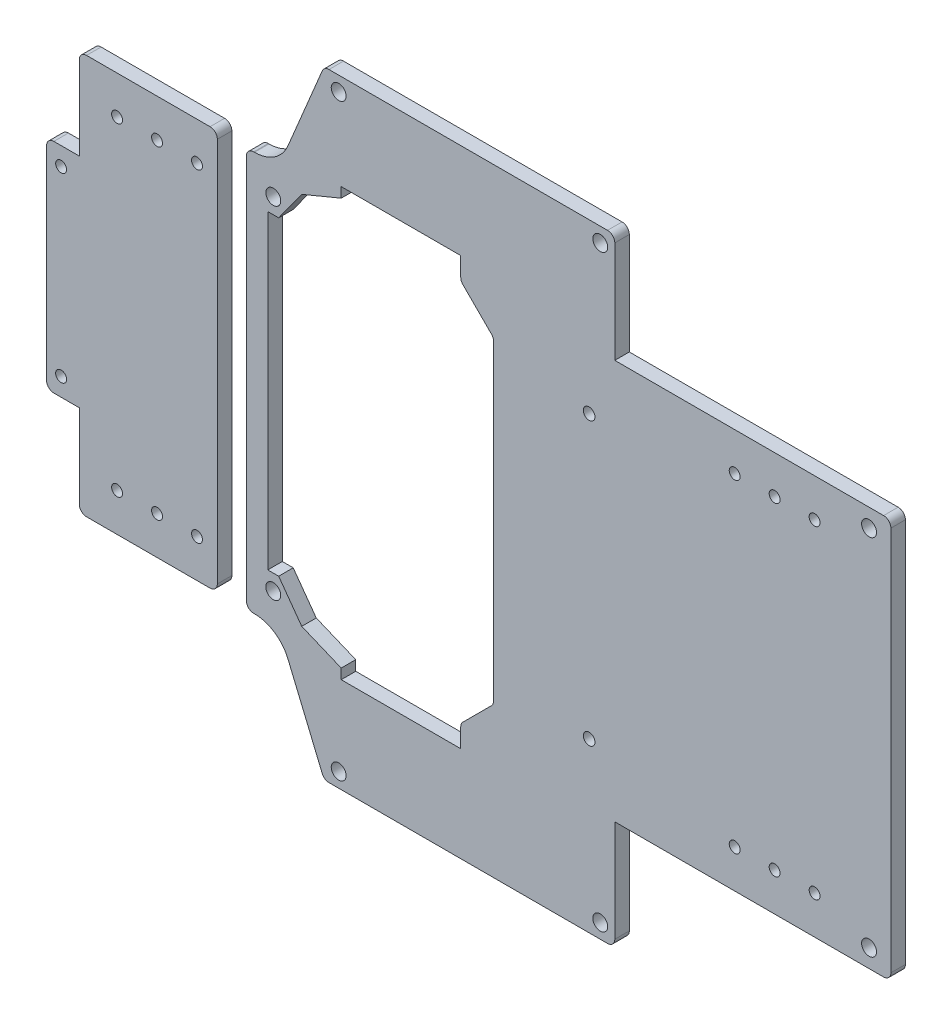
SolidWorks part; units mm, degrees
ref_plane "前视基准面" through (0, 0, 0) normal (0, 0, 1) x (1, 0, 0)
ref_plane "上视基准面" through (0, 0, 0) normal (0, 1, 0) x (1, 0, 0)
ref_plane "右视基准面" through (0, 0, 0) normal (1, 0, 0) x (0, 0, -1)
other "Configuration Table"
sketch "草图1" plane through (0, 0, 0) normal (0, 0, 1) x (1, 0, 0)
  line L16 (-45.366, -102.5649) -> (-42.366, -102.5649)
  line L17 (-45.366, -61.4682) -> (-45.366, -102.5649)
  line L18 (7.7514, -61.4682) -> (-45.366, -61.4682)
  line L19 (7.7514, -111.3467) -> (7.7514, -61.4682)
  line L20 (2.1538, -115.8547) -> (7.7514, -111.3467)
  line L21 (-25.1515, -115.8547) -> (2.1538, -115.8547)
  line L22 (-36.0216, -111.3467) -> (-25.1515, -115.8547)
  line L23 (-42.366, -102.5649) -> (-36.0216, -111.3467)
  line L32 (2.1538, -3.8547) -> (-25.1515, -3.8547)
  line L33 (7.7514, -8.3627) -> (2.1538, -3.8547)
  line L34 (7.7514, -58.2412) -> (7.7514, -8.3627)
  line L35 (-45.366, -58.2412) -> (7.7514, -58.2412)
  line L36 (-45.366, -17.1445) -> (-45.366, -58.2412)
  line L37 (-42.366, -17.1445) -> (-45.366, -17.1445)
  line L38 (-36.0216, -8.3627) -> (-42.366, -17.1445)
  line L39 (-25.1515, -3.8547) -> (-36.0216, -8.3627)
  line L48 (-97.2501, -29.8547) -> (-104.2501, -29.8547)
  line L49 (-106.2501, -31.8547) -> (-106.2501, -87.8547)
  line L50 (-104.2501, -89.8547) -> (-97.2501, -89.8547)
  line L51 (-97.2501, -89.8547) -> (-97.2501, -112.8547)
  line L52 (-95.2501, -114.8547) -> (-61.2501, -114.8547)
  line L53 (-59.2501, -112.8547) -> (-59.2501, -6.8547)
  line L54 (-61.2501, -4.8547) -> (-95.2501, -4.8547)
  line L55 (-97.2501, -6.8547) -> (-97.2501, -29.8547)
  line L72 (-51.2501, -6.8547) -> (-51.2501, -112.8547)
  line L73 (-49.2501, -114.8547) -> (-49.0398, -114.8547)
  line L74 (-39.8127, -120.9997) -> (-30.3597, -143.6257)
  line L75 (-28.5143, -144.8547) -> (48.1538, -144.8547)
  line L76 (50.1538, -142.8547) -> (50.1538, -114.8547)
  line L77 (50.1538, -114.8547) -> (124.1538, -114.8547)
  line L78 (126.1538, -112.8547) -> (126.1538, -6.8547)
  line L79 (124.1538, -4.8547) -> (50.1538, -4.8547)
  line L80 (50.1538, -4.8547) -> (50.1538, 23.1453)
  line L81 (48.1538, 25.1453) -> (-28.5143, 25.1453)
  line L82 (-30.3597, 23.9163) -> (-39.8127, 1.2903)
  line L83 (-49.0398, -4.8547) -> (-49.2501, -4.8547)
  arc A4 (105.1538, -105.8547) -> (105.1538, -102.8547) centre (105.1538, -104.3547) ccw
  arc A5 (105.1538, -102.8547) -> (105.1538, -105.8547) centre (105.1538, -104.3547) ccw
  arc A8 (94.1538, -16.8547) -> (94.1538, -13.8547) centre (94.1538, -15.3547) ccw
  arc A9 (94.1538, -13.8547) -> (94.1538, -16.8547) centre (94.1538, -15.3547) ccw
  arc A12 (-25.8462, -142.9047) -> (-25.8462, -138.8047) centre (-25.8462, -140.8547) ccw
  arc A13 (-25.8462, -138.8047) -> (-25.8462, -142.9047) centre (-25.8462, -140.8547) ccw
  arc A16 (-43.8462, -14.9047) -> (-43.8462, -10.8047) centre (-43.8462, -12.8547) ccw
  arc A17 (-43.8462, -10.8047) -> (-43.8462, -14.9047) centre (-43.8462, -12.8547) ccw
  arc A20 (46.1538, 19.0953) -> (46.1538, 23.1953) centre (46.1538, 21.1453) ccw
  arc A21 (46.1538, 23.1953) -> (46.1538, 19.0953) centre (46.1538, 21.1453) ccw
  arc A24 (120.1538, -11.9147) -> (120.1538, -7.7947) centre (120.1538, -9.8547) ccw
  arc A25 (120.1538, -7.7947) -> (120.1538, -11.9147) centre (120.1538, -9.8547) ccw
  arc A28 (83.1538, -16.8547) -> (83.1538, -13.8547) centre (83.1538, -15.3547) ccw
  arc A29 (83.1538, -13.8547) -> (83.1538, -16.8547) centre (83.1538, -15.3547) ccw
  arc A32 (105.1538, -16.8547) -> (105.1538, -13.8547) centre (105.1538, -15.3547) ccw
  arc A33 (105.1538, -13.8547) -> (105.1538, -16.8547) centre (105.1538, -15.3547) ccw
  arc A36 (83.1538, -105.8547) -> (83.1538, -102.8547) centre (83.1538, -104.3547) ccw
  arc A37 (83.1538, -102.8547) -> (83.1538, -105.8547) centre (83.1538, -104.3547) ccw
  arc A40 (94.1538, -105.8547) -> (94.1538, -102.8547) centre (94.1538, -104.3547) ccw
  arc A41 (94.1538, -102.8547) -> (94.1538, -105.8547) centre (94.1538, -104.3547) ccw
  arc A44 (120.1538, -111.9147) -> (120.1538, -107.7947) centre (120.1538, -109.8547) ccw
  arc A45 (120.1538, -107.7947) -> (120.1538, -111.9147) centre (120.1538, -109.8547) ccw
  arc A48 (-25.8462, 19.0953) -> (-25.8462, 23.1953) centre (-25.8462, 21.1453) ccw
  arc A49 (-25.8462, 23.1953) -> (-25.8462, 19.0953) centre (-25.8462, 21.1453) ccw
  arc A52 (-43.8462, -108.9047) -> (-43.8462, -104.8047) centre (-43.8462, -106.8547) ccw
  arc A53 (-43.8462, -104.8047) -> (-43.8462, -108.9047) centre (-43.8462, -106.8547) ccw
  arc A56 (46.1538, -142.9047) -> (46.1538, -138.8047) centre (46.1538, -140.8547) ccw
  arc A57 (46.1538, -138.8047) -> (46.1538, -142.9047) centre (46.1538, -140.8547) ccw
  arc A60 (43.0925, -97.0203) -> (43.0925, -100.2203) centre (43.0925, -98.6203) ccw
  arc A61 (43.0925, -100.2203) -> (43.0925, -97.0203) centre (43.0925, -98.6203) ccw
  arc A64 (43.0925, -19.4891) -> (43.0925, -22.6891) centre (43.0925, -21.0891) ccw
  arc A65 (43.0925, -22.6891) -> (43.0925, -19.4891) centre (43.0925, -21.0891) ccw
  arc A74 (-64.8462, -16.8547) -> (-64.8462, -13.8547) centre (-64.8462, -15.3547) ccw
  arc A75 (-64.8462, -13.8547) -> (-64.8462, -16.8547) centre (-64.8462, -15.3547) ccw
  arc A76 (-104.2501, -29.8547) -> (-106.2501, -31.8547) centre (-104.2501, -31.8547) ccw
  arc A77 (-106.2501, -87.8547) -> (-104.2501, -89.8547) centre (-104.2501, -87.8547) ccw
  arc A78 (-97.2501, -112.8547) -> (-95.2501, -114.8547) centre (-95.2501, -112.8547) ccw
  arc A79 (-61.2501, -114.8547) -> (-59.2501, -112.8547) centre (-61.2501, -112.8547) ccw
  arc A80 (-59.2501, -6.8547) -> (-61.2501, -4.8547) centre (-61.2501, -6.8547) ccw
  arc A81 (-95.2501, -4.8547) -> (-97.2501, -6.8547) centre (-95.2501, -6.8547) ccw
  arc A84 (-75.8462, -16.8547) -> (-75.8462, -13.8547) centre (-75.8462, -15.3547) ccw
  arc A85 (-75.8462, -13.8547) -> (-75.8462, -16.8547) centre (-75.8462, -15.3547) ccw
  arc A88 (-102.2501, -36.3547) -> (-102.2501, -33.3547) centre (-102.2501, -34.8547) ccw
  arc A89 (-102.2501, -33.3547) -> (-102.2501, -36.3547) centre (-102.2501, -34.8547) ccw
  arc A92 (-75.8462, -105.8547) -> (-75.8462, -102.8547) centre (-75.8462, -104.3547) ccw
  arc A93 (-75.8462, -102.8547) -> (-75.8462, -105.8547) centre (-75.8462, -104.3547) ccw
  arc A96 (-102.2501, -86.3547) -> (-102.2501, -83.3547) centre (-102.2501, -84.8547) ccw
  arc A97 (-102.2501, -83.3547) -> (-102.2501, -86.3547) centre (-102.2501, -84.8547) ccw
  arc A100 (-64.8462, -105.8547) -> (-64.8462, -102.8547) centre (-64.8462, -104.3547) ccw
  arc A101 (-64.8462, -102.8547) -> (-64.8462, -105.8547) centre (-64.8462, -104.3547) ccw
  arc A104 (-86.8462, -105.8547) -> (-86.8462, -102.8547) centre (-86.8462, -104.3547) ccw
  arc A105 (-86.8462, -102.8547) -> (-86.8462, -105.8547) centre (-86.8462, -104.3547) ccw
  arc A108 (-86.8462, -16.8547) -> (-86.8462, -13.8547) centre (-86.8462, -15.3547) ccw
  arc A109 (-86.8462, -13.8547) -> (-86.8462, -16.8547) centre (-86.8462, -15.3547) ccw
  arc A128 (-51.2501, -112.8547) -> (-49.2501, -114.8547) centre (-49.2501, -112.8547) ccw
  arc A129 (-39.8127, -120.9997) -> (-49.0398, -114.8547) centre (-49.0398, -124.8547) ccw
  arc A130 (-30.3597, -143.6257) -> (-28.5143, -144.8547) centre (-28.5143, -142.8547) ccw
  arc A131 (48.1538, -144.8547) -> (50.1538, -142.8547) centre (48.1538, -142.8547) ccw
  arc A132 (124.1538, -114.8547) -> (126.1538, -112.8547) centre (124.1538, -112.8547) ccw
  arc A133 (126.1538, -6.8547) -> (124.1538, -4.8547) centre (124.1538, -6.8547) ccw
  arc A134 (50.1538, 23.1453) -> (48.1538, 25.1453) centre (48.1538, 23.1453) ccw
  arc A135 (-28.5143, 25.1453) -> (-30.3597, 23.9163) centre (-28.5143, 23.1453) ccw
  arc A136 (-49.0398, -4.8547) -> (-39.8127, 1.2903) centre (-49.0398, 5.1453) ccw
  arc A137 (-49.2501, -4.8547) -> (-51.2501, -6.8547) centre (-49.2501, -6.8547) ccw
extrude "凸台-拉伸1" add sketch "草图1" against normal up to surface (4 mm away)
sketch "草图2" plane through (0, 0, 0) normal (0, 0, 1) x (1, 0, 0)
  line L0 (7.7514, -61.4682) -> (-45.366, -61.4682)
  line L1 (-45.366, -61.4682) -> (-45.366, -56.9371)
  line L2 (-45.366, -56.9371) -> (7.7514, -56.9371)
  line L3 (7.7514, -56.9371) -> (7.7514, -61.4682)
  line L4 (7.7514, -111.3467) -> (7.7514, -118.6299)
  line L5 (-25.1515, -115.8547) -> (-25.1515, -118.6299)
  line L6 (-25.1515, -118.6299) -> (7.7514, -118.6299)
  line L7 (7.7514, -111.3467) -> (-25.1515, -115.8547)
  line L8 (-106.2501, -59.8547) -> (133.6005, -59.8547) construction
  line L10 (7.7514, -8.3627) -> (-25.1515, -3.8547)
  line L11 (-25.1515, -1.0795) -> (7.7514, -1.0795)
  line L12 (-25.1515, -3.8547) -> (-25.1515, -1.0795)
  line L13 (7.7514, -8.3627) -> (7.7514, -1.0795)
extrude "切除-拉伸1" cut sketch "草图2" against normal up to next (4 mm away)
sketch "草图3" plane through (0, 0, 0) normal (0, 0, 1) x (1, 0, 0)
  line L0 (7.7514, -112.5975) -> (16.7766, -103.5723)
  line L1 (16.7766, -103.5723) -> (16.7766, -16.1371)
  line L2 (126.1538, -112.8547) -> (126.1538, -6.8547) construction
  line L3 (126.1538, -112.8547) -> (126.1538, -6.8547) construction
  line L4 (126.1538, -59.8547) -> (157.5088, -59.8547) construction
  line L5 (7.7514, -7.1119) -> (16.7766, -16.1371)
  line L6 (7.7514, -112.5975) -> (7.7514, -7.1119)
  point P11 (16.7766, -59.8547)
extrude "切除-拉伸2" cut sketch "草图3" against normal up to next (4 mm away)
fillet "圆角1" radius 2 4 edges at (16.7766, -103.5723, -2) (16.7766, -16.1371, -2) (7.7514, -7.1119, -2) (7.7514, -112.5975, -2)
